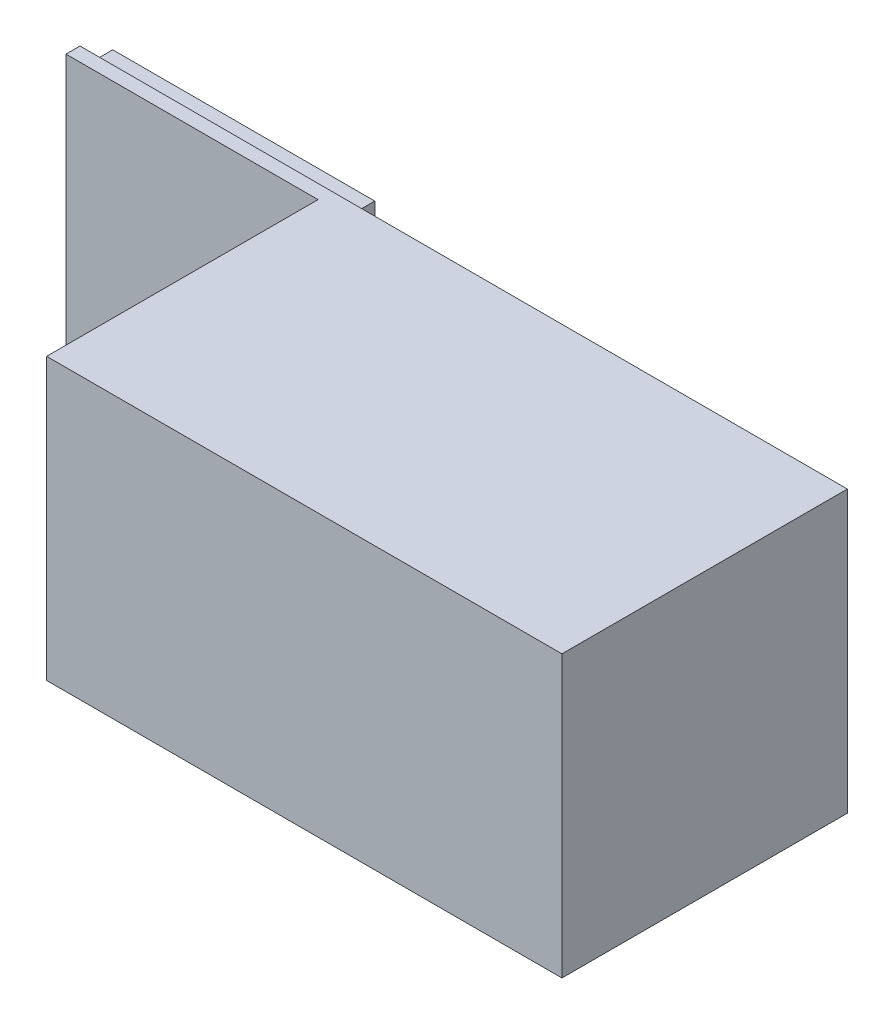
SolidWorks part; units mm, degrees
ref_plane "前基準面" through (0, 0, 0) normal (0, 0, 1) x (1, 0, 0)
ref_plane "上基準面" through (0, 0, 0) normal (0, 1, 0) x (1, 0, 0)
ref_plane "右基準面" through (0, 0, 0) normal (1, 0, 0) x (0, 0, -1)
sketch "草圖1" plane through (0, 0, 0) normal (0, 0, 1) x (1, 0, 0)
  line L1 (-41, 15) -> (41, 15)
  line L2 (-41, 15) -> (-41, -15)
  line L3 (-41, -15) -> (41, -15)
  line L4 (41, 15) -> (41, -15)
  line L5 (-41, 15) -> (41, -15) construction
  line L6 (-41, -15) -> (41, 15) construction
  point P0 (0, 0)
  dimension "D1" = 82
  dimension "D2" = 30
extrude "填料-伸長1" add sketch "草圖1" along normal blind 1.5
sketch "草圖2" plane through (0, 0, 0) normal (0, 0, -1) x (-1, 0, 0)
  line L0 (41, 12.8993) -> (41, -12.8993)
  line L1 (41, 15) -> (41, -15) construction
  line L2 (41, 12.8993) -> (39.0024, 12.8993)
  line L3 (39.0024, 12.8993) -> (39.0024, -12.8993)
  line L4 (39.0024, -12.8993) -> (41, -12.8993)
  point P5 (41, 0)
extrude "填料-伸長3" add sketch "草圖2" along normal blind 3.5
sketch "草圖4" plane through (-39.0024, 0, 0) normal (1, 0, 0) x (0, 0, -1)
  line L0 (0, 12.8993) -> (1.75, 12.8993)
  line L1 (3.5, 12.8993) -> (0, 12.8993) construction
  line L2 (1.75, 12.8993) -> (1.75, -12.8993)
  line L3 (3.5, -12.8993) -> (0, -12.8993) construction
  line L4 (1.75, -12.8993) -> (3.5, -12.8993)
  line L5 (3.5, -12.8993) -> (3.5, 12.8993)
  line L6 (3.5, 12.8993) -> (1.75, 12.8993)
  line M2 (0, -12.8993) -> (3.5, -12.8993)
  line M3 (3.5, -12.8993) -> (3.5, 12.8993)
  line M4 (3.5, 12.8993) -> (0, 12.8993)
extrude "填料-伸長4" add sketch "草圖4" along normal blind 26 contours L2 M4 M2 M3
sketch "草圖5" plane through (0, 0, 1.5) normal (0, 0, 1) x (1, 0, 0)
  line L0 (41, 15) -> (41, -15)
  line L1 (41, -15) -> (-14.0641, -15)
  line L2 (-41, -15) -> (41, -15) construction
  line L3 (-14.0641, -15) -> (-14.0641, 15)
  line L4 (41, 15) -> (-41, 15) construction
  line L5 (-14.0641, 15) -> (41, 15)
extrude "填料-伸長5" add sketch "草圖5" along normal blind 29
sketch "草圖6" plane through (-14.0641, 0, 0) normal (-1, 0, 0) x (0, 0, 1)
  line L0 (2.8174, 14.0374) -> (2.8174, -14.1576)
  line L3 (2.8174, 14.0374) -> (29.1701, 14.0374)
  line L4 (29.1701, 14.0374) -> (29.1701, -14.1576)
  line L5 (29.1701, -14.1576) -> (2.8174, -14.1576)
extrude "除料-伸長1" cut sketch "草圖6" against normal blind 53
sketch "草圖8" plane through (0, 0, 2.8174) normal (0, 0, 1) x (1, 0, 0)
  line L0 (-14.0641, 14.0374) -> (38.9359, 14.0374)
  line L1 (38.9359, 14.0374) -> (38.9359, -14.1576)
  line L2 (38.9359, -14.1576) -> (-14.0641, -14.1576) construction
  line L3 (38.9359, 14.0374) -> (38.9359, -14.1576) construction
  line L4 (38.9359, -14.1576) -> (-14.0641, -14.1576)
  line L5 (-14.0641, -14.1576) -> (-14.0641, 14.0374)
extrude "除料-伸長2" cut sketch "草圖8" against normal blind 1.32
